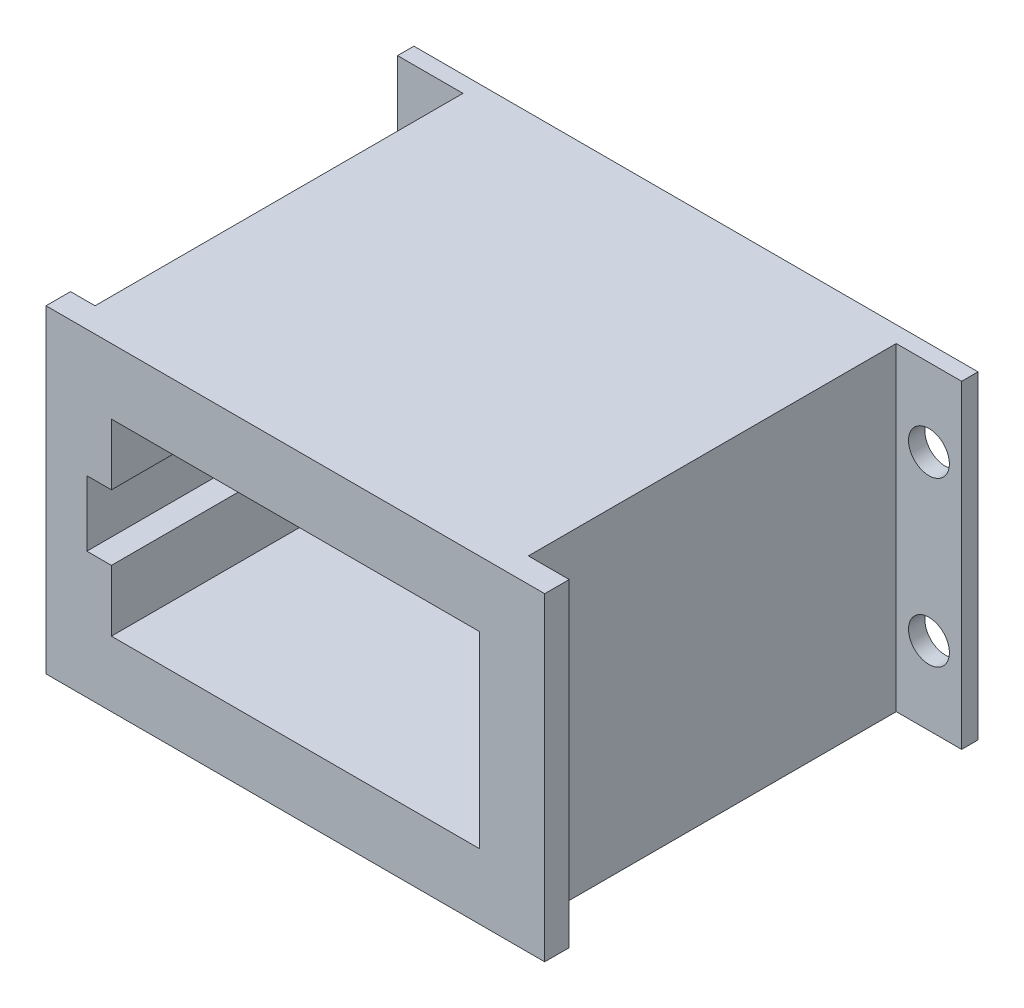
SolidWorks part; units mm, degrees
ref_plane "Front Plane" through (0, 0, 0) normal (0, 0, 1) x (1, 0, 0)
ref_plane "Top Plane" through (0, 0, 0) normal (0, 1, 0) x (1, 0, 0)
ref_plane "Right Plane" through (0, 0, 0) normal (1, 0, 0) x (0, 0, -1)
sketch "Sketch1" plane through (0, 0, 0) normal (0, 0, 1) x (1, 0, 0)
  line L0 (0, 0) -> (45, 0)
  line L1 (45, 0) -> (45, -23)
  line L2 (45, -23) -> (0, -23)
  line L3 (0, -23) -> (0, -15.5)
  line L4 (0, -7.5) -> (0, 0)
  line L5 (0, -7.5) -> (-3, -7.5)
  line L6 (0, -15.5) -> (-3, -15.5)
  line L7 (-3, -7.5) -> (-3, -15.5)
  line L8 (-8, 8) -> (53, 8)
  line L9 (53, 8) -> (53, -31)
  line L10 (53, -31) -> (-8, -31)
  line L11 (-8, -31) -> (-8, -23.5)
  line L12 (-8, 0.5) -> (-8, -23.5)
  line L15 (-8, 0.5) -> (-8, 8)
  line L16 (-11, 0.5) -> (-11, -23.5) construction
  line L17 (-8, 0.5) -> (-11, 0.5) construction
  line L18 (-8, -23.5) -> (-11, -23.5) construction
  dimension "D1" = 8
extrude "Boss-Extrude1" add sketch "Sketch1" along normal blind 50
sketch "Sketch2" plane through (0, 8, 0) normal (0, 1, 0) x (1, 0, 0)
  line L0 (22.5, 0) -> (22.5, -5.8116)
  line L1 (53, -50) -> (53, 0) construction
  line L2 (53, -2) -> (50, -2)
  line L3 (50, -2) -> (50, -47)
  line L4 (50, -47) -> (53, -47)
  line L5 (53, -47) -> (53, -2)
  line L6 (53, 0) -> (-8, 0) construction
  line L7 (-8, -47) -> (-8, -2)
  line L8 (-5, -47) -> (-8, -47)
  line L9 (-5, -2) -> (-5, -47)
  line L10 (-8, -2) -> (-5, -2)
  line M2 (-8, 0) -> (-8, -50)
  line M4 (53, -50) -> (53, 0)
extrude "Cut-Extrude1" cut sketch "Sketch2" against normal blind 50 contours L10 L8 L9 M2 | L3 L4 L2 M4
sketch "Sketch3" plane through (0, 8, 0) normal (0, 1, 0) x (1, 0, 0)
  line L0 (50, -2) -> (48, -2)
  line L1 (48, -2) -> (48, -47)
  line L2 (48, -47) -> (50, -47)
  line L3 (50, -47) -> (50, -2)
extrude "Cut-Extrude2" cut sketch "Sketch3" against normal through all
sketch "Sketch4" plane through (0, 8, 0) normal (0, 1, 0) x (1, 0, 0)
  line L0 (53, -2) -> (56, -2)
  line L1 (56, -2) -> (56, 0)
  line L2 (56, 0) -> (53, 0)
  line L3 (53, 0) -> (53, -2)
extrude "Boss-Extrude2" add sketch "Sketch4" against normal up to surface (39 mm away) up to face at (22.1667, -31, 24.6667)
sketch "Sketch5" plane through (0, 8, 0) normal (0, 1, 0) x (1, 0, 0)
  line L0 (-5, -2) -> (-13, -2)
  line L1 (-13, -2) -> (-13, 0)
  line L2 (-13, 0) -> (-5, 0)
  line L3 (56, 0) -> (-8, 0) construction
  line L4 (-5, 0) -> (-5, -2)
extrude "Boss-Extrude3" add sketch "Sketch5" against normal up to surface (39 mm away) up to face at (22.6667, -31, 24.6667)
sketch "Sketch6" plane through (0, 0, 0) normal (0, 0, -1) x (-1, 0, 0)
  line L2 (-56, -21.5) -> (-52, -21.5)
  line L3 (-56, -1.5) -> (-52, -1.5)
  line L4 (-21.5, 8) -> (-21.5, 4.8941)
  line L5 (-56, 8) -> (13, 8) construction
  line L6 (13, -21.5) -> (9, -21.5)
  line L7 (13, -1.5) -> (9, -1.5)
  circle A0 centre (-52, -1.5) radius 2.5
  circle A1 centre (-52, -21.5) radius 2.5
  circle A2 centre (9, -21.5) radius 2.5
  circle A3 centre (9, -1.5) radius 2.5
extrude "Cut-Extrude3" cut sketch "Sketch6" against normal up to next
